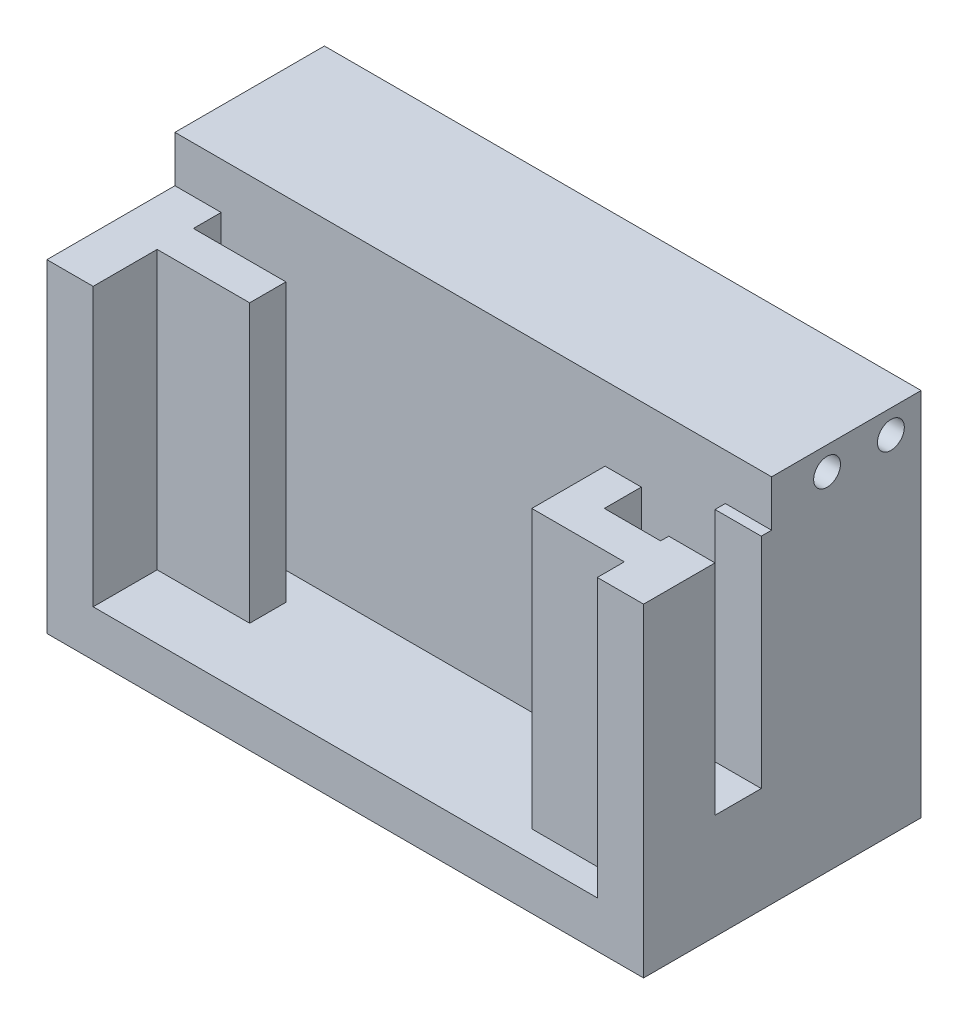
SolidWorks part; units mm, degrees
ref_plane "Plan de face" through (0, 0, 0) normal (0, 0, 1) x (1, 0, 0)
ref_plane "Plan de dessus" through (0, 0, 0) normal (0, 1, 0) x (1, 0, 0)
ref_plane "Plan de droite" through (0, 0, 0) normal (1, 0, 0) x (0, 0, -1)
sketch "Esquisse1" plane through (0, 0, 0) normal (0, 0, 1) x (1, 0, 0)
  line L1 (-35.5855, 20.1612) -> (18.9145, 20.1612)
  line L2 (-35.5855, 20.1612) -> (-35.5855, -9.8388)
  line L3 (-35.5855, -9.8388) -> (18.9145, -9.8388)
  line L4 (18.9145, 20.1612) -> (18.9145, -9.8388)
  dimension "D1" = 54.5
  dimension "D2" = 30
extrude "Boss.-Extru.8" add sketch "Esquisse1" along normal blind 5
sketch "Esquisse7" plane through (-35.5855, 0, 0) normal (-1, 0, 0) x (0, 0, 1)
  line L1 (0, 20.1612) -> (30, 20.1612)
  line L2 (0, 20.1612) -> (0, -9.8388)
  line L3 (0, -9.8388) -> (30, -9.8388)
  line L4 (30, 20.1612) -> (30, -9.8388)
  dimension "D1" = 30
extrude "Boss.-Extru.9" add sketch "Esquisse7" along normal blind 5
sketch "Esquisse8" plane through (18.9145, 0, 0) normal (1, 0, 0) x (0, 0, -1)
  line L1 (0, 20.1612) -> (-30, 20.1612)
  line L2 (0, 20.1612) -> (0, -9.8388)
  line L3 (0, -9.8388) -> (-30, -9.8388)
  line L4 (-30, 20.1612) -> (-30, -9.8388)
extrude "Boss.-Extru.10" add sketch "Esquisse8" along normal blind 5
sketch "Esquisse9" plane through (0, -9.8388, 0) normal (0, -1, 0) x (1, 0, 0)
  line L0 (-40.5855, 0) -> (23.9145, 0) construction
  line L1 (-40.5855, 30) -> (23.9145, 30)
  line L2 (-40.5855, 30) -> (-40.5855, 0)
  line L3 (-40.5855, 0) -> (23.9145, 0)
  line L4 (23.9145, 30) -> (23.9145, 0)
extrude "Boss.-Extru.11" add sketch "Esquisse9" along normal blind 5
sketch "Esquisse10" plane through (-35.5855, 0, 0) normal (1, 0, 0) x (0, 0, -1)
  line L0 (-30, 20.1612) -> (-5, 20.1612) construction
  line L1 (-16.162, 20.1612) -> (-11.162, 20.1612)
  line L2 (-16.162, 20.1612) -> (-16.162, -9.8388)
  line L3 (-16.162, -9.8388) -> (-11.162, -9.8388)
  line L4 (-11.162, 20.1612) -> (-11.162, -9.8388)
  line L5 (-5, -9.8388) -> (-30, -9.8388) construction
  dimension "D1" = 5
extrude "Boss.-Extru.12" add sketch "Esquisse10" along normal blind 55 contours L2 L1 L4 L3
sketch "Esquisse11" plane through (0, 20.1612, 0) normal (0, 1, 0) x (1, 0, 0)
  line L0 (23.9145, 0) -> (23.9145, -30) construction
  line L1 (-40.5855, 0) -> (23.9145, 0)
  line L2 (-40.5855, 0) -> (-40.5855, -16.162)
  line L3 (-40.5855, -16.162) -> (23.9145, -16.162)
  line L4 (23.9145, 0) -> (23.9145, -16.162)
extrude "Boss.-Extru.13" add sketch "Esquisse11" along normal blind 5
sketch "Esquisse13" plane through (-35.5855, 0, 0) normal (1, 0, 0) x (0, 0, -1)
  line L0 (-30, 20.1612) -> (-16.162, 20.1612) construction
  line L1 (-23.081, 20.1612) -> (-19.162, 20.1612)
  line L2 (-23.081, 20.1612) -> (-23.081, -9.8388)
  line L3 (-23.081, -9.8388) -> (-19.162, -9.8388)
  line L4 (-19.162, 20.1612) -> (-19.162, -9.8388)
  line L5 (-16.162, -9.8388) -> (-30, -9.8388) construction
  line L6 (-19.162, 5.1612) -> (-16.162, 5.1612) construction
  line L7 (-16.162, 20.1612) -> (-16.162, -9.8388) construction
  dimension "D1" = 3.919
extrude "Boss.-Extru.14" add sketch "Esquisse13" along normal blind 10
sketch "Esquisse16" plane through (18.9145, 0, 0) normal (-1, 0, 0) x (0, 0, 1)
  line L0 (16.162, 5.1612) -> (23.162, 5.1612) construction
  line L1 (16.162, 20.1612) -> (16.162, -9.8388) construction
  line L2 (16.162, 20.1612) -> (30, 20.1612) construction
  line L3 (23.162, 20.1612) -> (27.081, 20.1612)
  line L4 (23.162, 20.1612) -> (23.162, -9.8388)
  line L5 (23.162, -9.8388) -> (27.081, -9.8388)
  line L6 (27.081, 20.1612) -> (27.081, -9.8388)
  line L7 (30, -9.8388) -> (16.162, -9.8388) construction
  dimension "D1" = 3.919
extrude "Boss.-Extru.15" add sketch "Esquisse16" along normal blind 10
sketch "Esquisse17" plane through (0, 0, 23.162) normal (0, 0, -1) x (-1, 0, 0)
  line L0 (-8.9145, -9.8388) -> (-18.9145, -9.8388) construction
  line L1 (-8.9145, 20.1612) -> (-12.8335, 20.1612)
  line L2 (-8.9145, 20.1612) -> (-8.9145, -9.8388)
  line L3 (-8.9145, -9.8388) -> (-12.8335, -9.8388)
  line L4 (-12.8335, 20.1612) -> (-12.8335, -9.8388)
  dimension "D1" = 3.919
extrude "Boss.-Extru.16" add sketch "Esquisse17" along normal blind 4
sketch "Esquisse20" plane through (18.9145, 0, 0) normal (-1, 0, 0) x (0, 0, 1)
  line L0 (16.162, 20.1612) -> (23.162, 20.1612) construction
  line L1 (17.2767, 20.1612) -> (22.2767, 20.1612)
  line L2 (17.2767, 20.1612) -> (17.2767, -3.4639)
  line L3 (17.2767, -3.4639) -> (22.2767, -3.4639)
  line L4 (22.2767, 20.1612) -> (22.2767, -3.4639)
  dimension "D1" = 5
extrude "Enlèv. mat.-Extru.2" cut sketch "Esquisse20" against normal blind 7
sketch "Esquisse21" plane through (-40.5855, 0, 0) normal (-1, 0, 0) x (0, 0, 1)
  line L0 (16.162, 20.1612) -> (0, 20.1612) construction
  line L1 (0, 25.1612) -> (0, -14.8388) construction
  line L2 (4.7156, 22.6323) -> (8.7156, 22.6323) construction
  line L4 (1.8156, 22.6323) -> (0, 22.6323) construction
  line L5 (0, 24.1388) -> (0, 25.2177) construction
  line L6 (3.2656, 24.0823) -> (3.2656, 25.1612) construction
  line L7 (0, 25.1612) -> (16.162, 25.1612) construction
  circle A0 centre (3.2656, 22.6323) radius 1.45
  circle A1 centre (10.1656, 22.6323) radius 1.45
extrude "Enlèv. mat.-Extru.3" cut sketch "Esquisse21" against normal blind 7
sketch "Esquisse22" plane through (23.9145, 0, 0) normal (1, 0, 0) x (0, 0, -1)
  line L2 (-8.7156, 22.6323) -> (-4.7156, 22.6323) construction
  line L4 (-1.8156, 22.6323) -> (0, 22.6323) construction
  line L5 (0, -14.8388) -> (0, 25.1612) construction
  circle A0 centre (-3.2656, 22.6323) radius 1.45
  circle A1 centre (-10.1656, 22.6323) radius 1.45
extrude "Enlèv. mat.-Extru.4" cut sketch "Esquisse22" against normal blind 7
